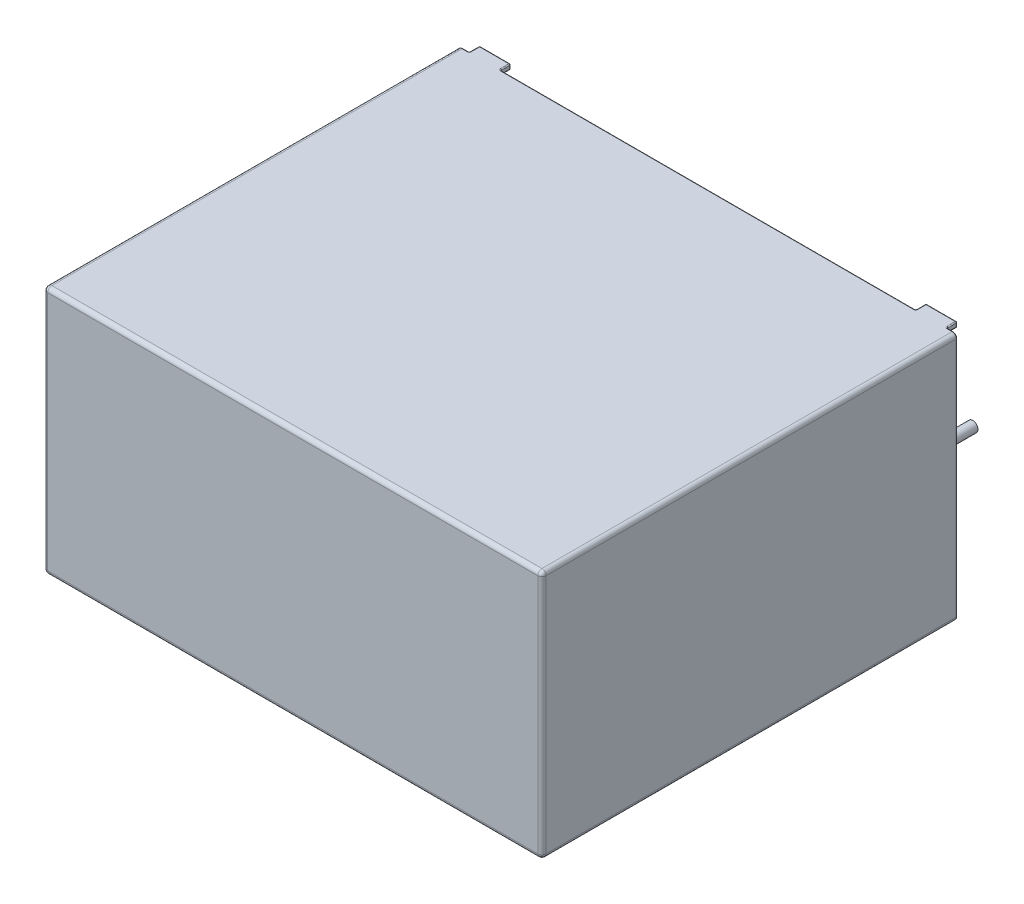
SolidWorks part; units mm, degrees
ref_plane "Vorne Links" through (0, 0, 0) normal (0, 0, 1) x (1, 0, 0)
ref_plane "Oben" through (0, 0, 0) normal (0, 1, 0) x (1, 0, 0)
ref_plane "Vorne Rechts" through (0, 0, 0) normal (1, 0, 0) x (0, 0, -1)
sketch "Skizze1" plane through (0, 0, 0) normal (0, 0, -1) x (1, 0, 0)
  line L0 (0, 0) -> (0, 1.7483) construction
  line L1 (-11.8, -6) -> (11.8, -6)
  line L2 (-12, -5.8) -> (-12, 5.8)
  line L3 (-11.8, 6) -> (11.8, 6)
  line L4 (12, -5.8) -> (12, 5.8)
  line L5 (0, 0) -> (-1.4025, 0) construction
  arc A0 (-12, -5.8) -> (-11.8, -6) centre (-11.8, -5.8) ccw
  arc A1 (-11.8, 6) -> (-12, 5.8) centre (-11.8, 5.8) ccw
  arc A2 (12, 5.8) -> (11.8, 6) centre (11.8, 5.8) ccw
  arc A3 (12, -5.8) -> (11.8, -6) centre (11.8, -5.8) cw
  point P7 (0, 0)
  point P10 (-12, 6)
  point P15 (7.2, 0)
  dimension "D3" = 0.2
  dimension "D1" = 24
  dimension "D2" = 12
extrude "Basis-Linear austragen" add sketch "Skizze1" against normal blind 20.5
sketch "Sketch3" plane through (0, 0, 0) normal (0, 0, -1) x (-1, 0, 0)
  line L5 (-12, 5.8) -> (-12, -5.8) construction
  line L6 (-11.625, 5.75) -> (11.625, 5.75)
  line L8 (-11.75, 5.625) -> (-11.75, -5.625)
  line L9 (-11.625, -5.75) -> (11.625, -5.75)
  line L10 (11.75, 5.625) -> (11.75, -5.625)
  line L11 (-11.75, 5.75) -> (11.75, -5.75) construction
  line L12 (-11.75, -5.75) -> (11.75, 5.75) construction
  line L13 (11.8, 6) -> (-11.8, 6) construction
  arc A4 (11.625, 5.75) -> (11.75, 5.625) centre (11.625, 5.625) cw
  arc A5 (11.625, -5.75) -> (11.75, -5.625) centre (11.625, -5.625) ccw
  arc A6 (-11.75, -5.625) -> (-11.625, -5.75) centre (-11.625, -5.625) ccw
  arc A7 (-11.625, 5.75) -> (-11.75, 5.625) centre (-11.625, 5.625) ccw
  point P0 (0, 0)
  dimension "D3" = 0.125
  dimension "D1" = 0.25
  dimension "D2" = 0.25
extrude "Cut-Extrude1" cut sketch "Sketch3" against normal blind 0.7
fillet "Fillet1" radius 0.05 8 edges at (-11.75, 0, 0.7) (-11.7134, -5.7134, 0.7) (0, -5.75, 0.7) (11.7134, -5.7134, 0.7) (11.75, 0, 0.7) (11.7134, 5.7134, 0.7) (0, 5.75, 0.7) (-11.7134, 5.7134, 0.7)
fillet "Verrundung1" radius 0.2 8 edges at (-12, 0, 20.5) (-11.9414, -5.9414, 20.5) (0, -6, 20.5) (11.9414, -5.9414, 20.5) (12, 0, 20.5) (11.9414, 5.9414, 20.5) (0, 6, 20.5) (-11.9414, 5.9414, 20.5)
sketch "Skizze3" plane through (0, -6, 0) normal (0, 1, 0) x (1, 0, 0)
  line L0 (11.8, -20.5) -> (-11.8, -20.5) construction
  line L2 (-3.3067, -17.5) -> (3.3067, -17.5) construction
  text T0 "WIMA" font "Arial" height 1.5
  point P3 (0, -20.5)
  point P4 (-3.3067, -17.5)
  point P9 (0, -17.5)
  dimension "D1" = 3
sketch "Sketch4" plane through (0, 6, 0) normal (0, 1, 0) x (1, 0, 0)
  line L1 (-10, -0.5) -> (10, -0.5)
  line L2 (-10, -0.5) -> (-10, 0)
  line L3 (-10, 0) -> (10, 0)
  line L4 (12, -0.5) -> (12, 0)
  line L6 (-11.5, 0) -> (-12, 0)
  line L7 (-11.5, 0) -> (-11.5, -0.5)
  line L8 (-11.5, -0.5) -> (-12, -0.5)
  line L9 (-12, 0) -> (-12, -0.5)
  line L11 (10, -0.5) -> (10, 0)
  line L13 (11.5, -0.5) -> (11.5, 0)
  line L14 (11.5, 0) -> (12, 0)
  line L15 (11.5, -0.5) -> (12, -0.5)
  line L16 (-12, -20.3) -> (-12, 0) construction
  line L17 (12, -20.3) -> (12, 0) construction
  line L18 (11.8, 0) -> (-11.8, 0) construction
  point P5 (0, 0)
  point P18 (-4.5, 0.5)
  point P21 (0, 0)
  dimension "D1" = 0.5
  dimension "D2" = 0.5
  dimension "D3" = 1.5
extrude "Cut-Extrude2" cut sketch "Sketch4" against normal blind 30
sketch "Skizze2" plane through (0, 0, 0.7) normal (0, 0, -1) x (-1, 0, 0)
  line L0 (-10.25, 0) -> (10.25, 0) construction
  circle A0 centre (-10.25, 0) radius 0.25
  circle A1 centre (10.25, 0) radius 0.25
  point P0 (9.4894, 3.7715)
  point P1 (0, 0)
  point P2 (0, 0)
  dimension "D1" = 20.5
  dimension "D2" = 0.5
extrude "Aufsatz-Linear austragen1" add sketch "Skizze2" along normal blind 2.7
fillet "Fillet2" radius 0.05 64 edges at (-10, 5.75, 0.25) (-10, -5.75, 0.25) (10, 6, 0.25) (10, -6, 0.25) (-11.5, -6, 0.25) (-11.5, 6, 0.25) (-10, 6, 0.25) (-10, -6, 0.25) (-12, 0, 0.5) (-11.9414, -5.9414, 0.5) (-11.65, -6, 0.5) (-11.5, 5.875, 0.5) (-11.5, -5.875, 0.5) (-11.65, 6, 0.5) (-11.9414, 5.9414, 0.5) (0, 6, 0.5) (-10, 5.875, 0.5) (-10.75, 5.75, 0) (-10, 5.875, 0) (-10.75, 6, 0) (-11.5, 5.875, 0) (-10.75, -6, 0) (-10, -5.875, 0) (-10.75, -5.75, 0) (-11.5, -5.875, 0) (-10, -5.875, 0.5) (0, -6, 0.5) (10, 5.75, 0.25) (10, -5.75, 0.25) (-11.5, -5.75, 0.25) (-11.5, 5.75, 0.25) (-11.5625, -5.75, 0.5) (-11.7134, -5.7134, 0.5) (-11.75, 0, 0.5) (-11.7134, 5.7134, 0.5) (-11.5625, 5.75, 0.5) (0, 5.75, 0.5) (0, -5.75, 0.5) (10.75, 6, 0) (10, 5.875, 0) (10.75, 5.75, 0) (11.5, 5.875, 0) (10, 5.875, 0.5) (10.75, -5.75, 0) (10, -5.875, 0) (10.75, -6, 0) (11.5, -5.875, 0) (10, -5.875, 0.5) (11.5, 6, 0.25) (11.5, 5.75, 0.25) (11.65, 6, 0.5) (11.5, 5.875, 0.5) (11.5625, 5.75, 0.5) (11.7134, 5.7134, 0.5) (11.75, 0, 0.5) (12, 0, 0.5) (11.9414, 5.9414, 0.5) (11.5, -5.75, 0.25) (11.5, -6, 0.25) (11.9414, -5.9414, 0.5) (11.7134, -5.7134, 0.5) (11.5625, -5.75, 0.5) (11.5, -5.875, 0.5) (11.65, -6, 0.5)
fillet "Fillet6" radius 0.1 2 edges at (10.25, -0.25, 0.7) (-10.25, -0.25, 0.7)
extrude "Boss-Extrude1" add sketch "Skizze3" against normal blind 0.05
